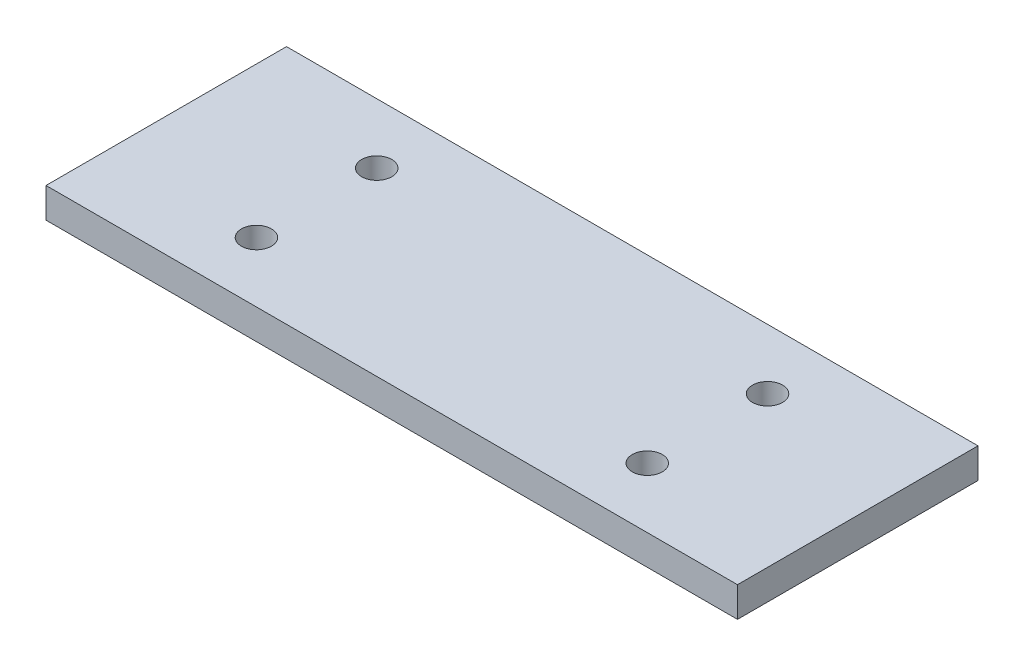
SolidWorks part; units mm, degrees
ref_plane "Front Plane" through (0, 0, 0) normal (0, 0, 1) x (1, 0, 0)
ref_plane "Top Plane" through (0, 0, 0) normal (0, 1, 0) x (1, 0, 0)
ref_plane "Right Plane" through (0, 0, 0) normal (1, 0, 0) x (0, 0, -1)
sketch "Sketch1" plane through (0, 0, 0) normal (0, 1, 0) x (1, 0, 0)
  line L1 (-57.5, 20) -> (57.5, 20)
  line L2 (-57.5, 20) -> (-57.5, -20)
  line L3 (-57.5, -20) -> (57.5, -20)
  line L4 (57.5, 20) -> (57.5, -20)
  line L5 (-57.5, 20) -> (57.5, -20) construction
  line L6 (-57.5, -20) -> (57.5, 20) construction
  point P0 (0, 0)
  dimension "D1" = 115
  dimension "D2" = 40
extrude "Boss-Extrude1" add sketch "Sketch1" along normal mid plane 5
hole_wizard "Hole1" positions "Sketch2" profile "Sketch3" legacy end condition through all
sketch "Sketch2" plane through (0, 2.5, 0) normal (0, 1, 0) x (1, 0, 0)
  point P0 (32.5, 10)
  point P2 (32.5, -10)
  dimension "D1" = 20
  dimension "D2" = 10
  dimension "D3" = 32.5
sketch "Sketch3" plane through (32.5, 2.5, -10) normal (1, 0, 0) x (0, 0, 1)
  line L0 (0, 0) -> (0, 5)
  line L1 (0, 5) -> (2.5, 5)
  line L2 (2.5, 5) -> (2.5, 0)
  line L3 (2.5, 0) -> (0, 0)
  line L4 (0, 110) -> (0, -10) construction
  dimension "Diameter" = 5
  dimension "Depth" = 5
mirror "Mirror1" about plane through (0, 0, 0) normal (1, 0, 0) of "Hole1"
